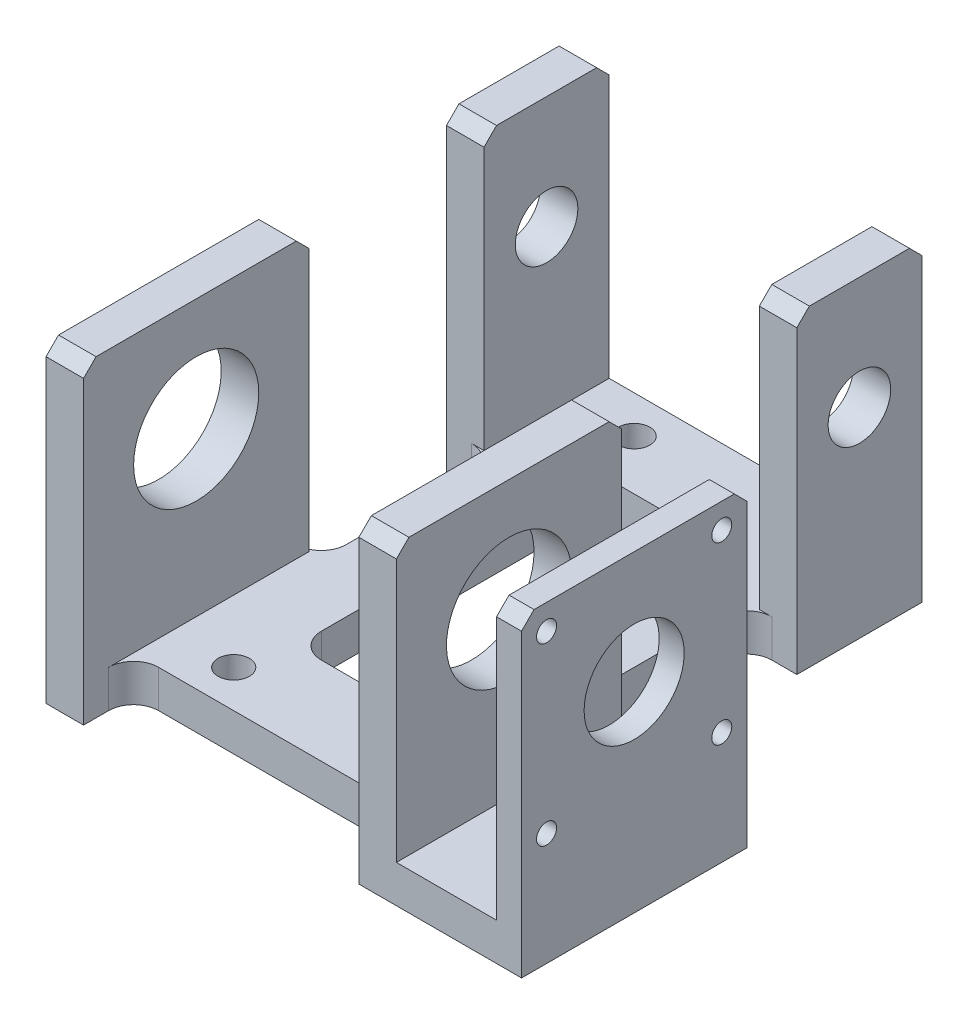
SolidWorks part; units mm, degrees
material "6061-T6 (SS)"
ref_plane "前视基准面" through (0, 0, 0) normal (0, 0, 1) x (1, 0, 0)
ref_plane "上视基准面" through (0, 0, 0) normal (0, 1, 0) x (1, 0, 0)
ref_plane "右视基准面" through (0, 0, 0) normal (1, 0, 0) x (0, 0, -1)
sketch "草图1" plane through (0, 0, 0) normal (0, 0, 1) x (1, 0, 0)
  line L0 (0, 0) -> (0, 25)
  line L1 (0, 25) -> (3, 25)
  line L2 (3, 25) -> (3, 3)
  line L3 (3, 3) -> (25, 3)
  line L4 (25, 3) -> (25, 25)
  line L5 (25, 25) -> (28, 25)
  line L6 (28, 25) -> (28, 0)
  line L7 (28, 0) -> (0, 0)
  line L8 (3, 25) -> (25, 25) construction
  dimension "D1" = 3
  dimension "D2" = 3
  dimension "D3" = 3
  dimension "D4" = 25
  dimension "D5" = 22
extrude "凸台-拉伸1" add sketch "草图1" along normal blind 42
sketch "草图2" plane through (28, 0, 0) normal (1, 0, 0) x (0, 0, -1)
  line L0 (0, 16) -> (-33, 16) construction
  line L1 (0, 0) -> (0, 25) construction
  line L2 (-42, 25) -> (0, 25) construction
  circle A0 centre (-5, 16) radius 2.5
  circle A1 centre (-33, 16) radius 5
  dimension "D1" = 5
  dimension "D3" = 28
  dimension "D4" = 5
  dimension "D5" = 10
  dimension "D2" = 9
extrude "切除-拉伸1" cut sketch "草图2" against normal through all
sketch "草图3" plane through (0, 0, 42) normal (0, 0, 1) x (1, 0, 0)
  line L0 (28, 0) -> (38, 0)
  line L1 (38, 0) -> (38, 25)
  line L2 (38, 25) -> (36, 25)
  line L3 (36, 25) -> (36, 3)
  line L4 (36, 3) -> (28, 3)
  line L5 (28, 0) -> (28, 25) construction
  line L6 (25, 3) -> (28, 3) construction
  line L7 (28, 3) -> (28, 0)
  line L8 (28, 25) -> (36, 25) construction
  dimension "D1" = 2
  dimension "D2" = 10
extrude "凸台-拉伸2" add sketch "草图3" against normal blind 18
sketch "草图5" plane through (36, 0, 0) normal (-1, 0, 0) x (0, 0, 1)
  circle A0 centre (33, 16) radius 4
  dimension "D1" = 8
extrude "切除-拉伸2" cut sketch "草图5" against normal through all
sketch "草图7" plane through (0, 3, 0) normal (0, 1, 0) x (1, 0, 0)
  line L0 (14, 0) -> (14, -42) construction
  line L1 (25, 0) -> (3, 0) construction
  line L2 (25, -42) -> (3, -42) construction
  line L4 (8, -3) -> (20, -3) construction
  line L5 (8, -3) -> (8, -35) construction
  line L6 (8, -35) -> (20, -35) construction
  line L7 (20, -3) -> (20, -35) construction
  line L8 (8, -3) -> (20, -35) construction
  line L9 (8, -35) -> (20, -3) construction
  point P6 (14, -19)
  dimension "D1" = 12
  dimension "D2" = 32
  dimension "D3" = 3
hole_wizard "M3 螺纹孔1" positions "3D草图1" profile "草图8" tap size "M3" standard "GB"
sketch3d "3D草图1"
  point P0 (20, 3, 3)
  point P3 (8, 3, 3)
  point P8 (20, 3, 35)
  point P19 (8, 3, 35)
sketch "草图8" plane through (20, 3, 3) normal (1, 0, 0) x (0, 0, 1)
  line L0 (0, 0) -> (0, 8.2511)
  line L1 (0, 8.2511) -> (1.25, 7.5)
  line L2 (1.25, 7.5) -> (1.25, 0)
  line L5 (1.25, 0) -> (0, 0)
  line L10 (0, 8.2511) -> (-1.25, 7.5) construction
  line L11 (0, -6.35) -> (0, 107.95) construction
  dimension "螺纹孔钻头直径" = 2.5
  dimension "螺纹孔钻头深度" = 7.5
  dimension "导头角度" = 118
cosmetic thread "孔螺蚊线8" parameters "D1"=3, "D2"=3
cosmetic thread "孔螺蚊线9" parameters "D1"=3, "D2"=3
cosmetic thread "孔螺蚊线10" parameters "D1"=3, "D2"=3
cosmetic thread "孔螺蚊线11" parameters "D1"=3, "D2"=3
sketch "草图9" plane through (0, 3, 0) normal (0, 1, 0) x (1, 0, 0)
  line L1 (3, -42) -> (25, -42)
  line L2 (3, -42) -> (3, -38)
  line L3 (3, -38) -> (25, -38)
  line L4 (25, -42) -> (25, -38)
  dimension "D1" = 4
extrude "切除-拉伸4" cut sketch "草图9" against normal through all
fillet "圆角1" radius 2 2 edges at (3, 1.5, 38) (25, 1.5, 38)
sketch "草图10" plane through (0, 3, 0) normal (0, 1, 0) x (1, 0, 0)
  line L0 (14, 0) -> (14, -38) construction
  line L1 (25, 0) -> (3, 0) construction
  line L2 (23, -38) -> (5, -38) construction
  line L4 (9, -7) -> (19, -7)
  line L5 (9, -7) -> (9, -31)
  line L6 (9, -31) -> (19, -31)
  line L7 (19, -7) -> (19, -31)
  line L8 (9, -7) -> (19, -31) construction
  line L9 (9, -31) -> (19, -7) construction
  point P6 (14, -19)
  dimension "D1" = 10
  dimension "D2" = 24
extrude "切除-拉伸5" cut sketch "草图10" against normal through all
fillet "圆角2" radius 2 4 edges at (19, 1.5, 31) (9, 1.5, 31) (19, 1.5, 7) (9, 1.5, 7)
sketch "草图11" plane through (0, 25, 0) normal (0, 1, 0) x (1, 0, 0)
  line L1 (28, -24) -> (24, -24)
  line L2 (28, -24) -> (28, -10)
  line L3 (28, -10) -> (24, -10)
  line L4 (24, -24) -> (24, -10)
  line L6 (4, -10) -> (0, -10)
  line L7 (4, -10) -> (4, -24)
  line L8 (4, -24) -> (0, -24)
  line L9 (0, -10) -> (0, -24)
  line L10 (0, -42) -> (0, 0) construction
  line L11 (28, 0) -> (25, 0) construction
  line L12 (4, -10) -> (24, -10) construction
  line L13 (24, -24) -> (4, -24) construction
  dimension "D1" = 10
  dimension "D2" = 4
extrude "切除-拉伸8" cut sketch "草图11" against normal through all
fillet "圆角3" radius 2 4 edges at (4, 1.5, 10) (4, 1.5, 24) (24, 1.5, 24) (24, 1.5, 10)
sketch "草图12" plane through (0, 25, 0) normal (0, 1, 0) x (1, 0, 0)
  line L0 (0, -24) -> (2, -24) construction
  line L1 (28, -10) -> (0, -10)
  line L2 (28, -10) -> (28, -24)
  line L3 (28, -24) -> (0, -24)
  line L4 (0, -10) -> (0, -24)
  line L5 (0, -42) -> (0, -24) construction
extrude "切除-拉伸9" cut sketch "草图12" against normal up to surface (22 mm away) up to face at (14, 3, 19)
sketch "草图13" plane through (38, 0, 0) normal (1, 0, 0) x (0, 0, -1)
  line L1 (-40, 23) -> (-26, 23) construction
  line L2 (-40, 23) -> (-40, 9) construction
  line L3 (-40, 9) -> (-26, 9) construction
  line L4 (-26, 23) -> (-26, 9) construction
  line L5 (-40, 23) -> (-26, 9) construction
  line L6 (-40, 9) -> (-26, 23) construction
  point P0 (-33, 16)
  dimension "D1" = 14
hole_wizard "M2 螺纹孔1" positions "3D草图2" profile "草图14" tap size "M2" standard "GB"
sketch3d "3D草图2"
  point P0 (38, 23, 40)
  point P3 (38, 23, 26)
  point P6 (38, 9, 26)
  point P9 (38, 9, 40)
sketch "草图14" plane through (38, 23, 40) normal (0, 1, 0) x (0, 0, -1)
  line L0 (0, 0) -> (0, 4.4807)
  line L1 (0, 4.4807) -> (0.8, 4)
  line L2 (0.8, 4) -> (0.8, 0)
  line L5 (0.8, 0) -> (0, 0)
  line L10 (0, 4.4807) -> (-0.8, 4) construction
  line L11 (0, -6.35) -> (0, 107.95) construction
  dimension "螺纹孔钻头直径" = 1.6
  dimension "螺纹孔钻头深度" = 4
  dimension "导头角度" = 118
cosmetic thread "孔螺蚊线12" parameters "D1"=2, "D2"=2
cosmetic thread "孔螺蚊线13" parameters "D1"=2, "D2"=2
cosmetic thread "孔螺蚊线14" parameters "D1"=2, "D2"=2
cosmetic thread "孔螺蚊线15" parameters "D1"=2, "D2"=2
fillet "圆角4" [suppressed] radius 1
chamfer "倒角1" distance 1 angle 45 10 edges at (1.5, 25, 10) (1.5, 25, 0) (26.5, 25, 0) (26.5, 25, 10) (37, 25, 24) (1.5, 25, 24) (26.5, 25, 24) (26.5, 25, 42) (37, 25, 42) (1.5, 25, 42)
